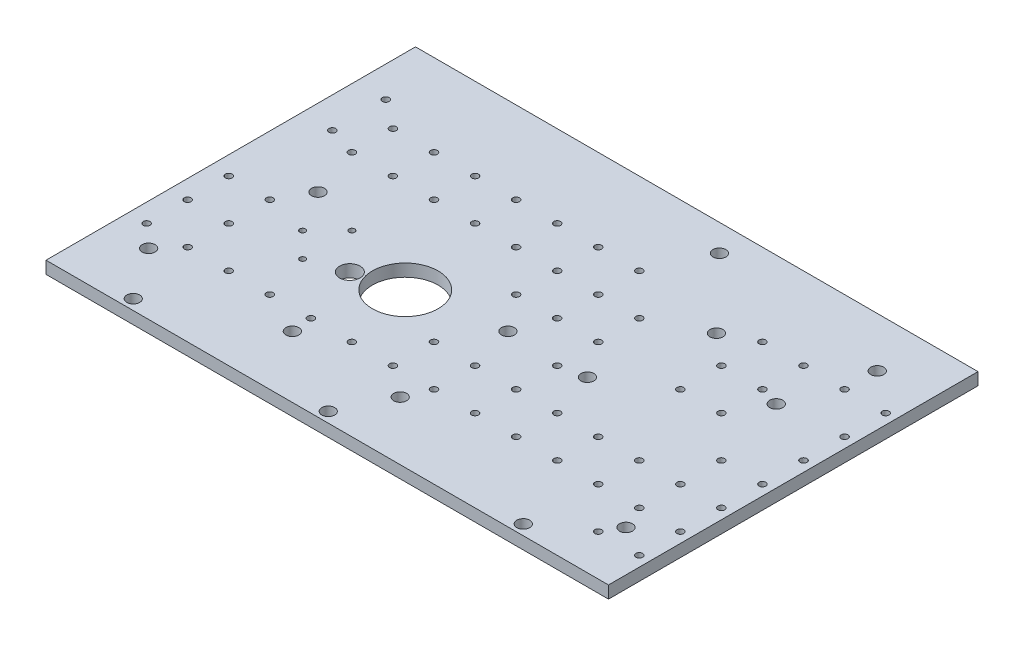
SolidWorks part; units mm, degrees
ref_plane "Front Plane" through (0, 0, 0) normal (0, 0, 1) x (1, 0, 0)
ref_plane "Top Plane" through (0, 0, 0) normal (0, 1, 0) x (1, 0, 0)
ref_plane "Right Plane" through (0, 0, 0) normal (1, 0, 0) x (0, 0, -1)
sketch "Sketch1" plane through (0, 0, 0) normal (0, 1, 0) x (1, 0, 0)
  line L0 (0, 0) -> (-137, 0) construction
  line L1 (-137, 90) -> (137, 90)
  line L2 (-137, 90) -> (-137, -90)
  line L3 (-137, -90) -> (137, -90)
  line L4 (137, 90) -> (137, -90)
  line L5 (-137, 90) -> (137, -90) construction
  line L6 (-137, -90) -> (137, 90) construction
  line L7 (-137, 25) -> (-137, -25)
  line L11 (-137, 25) -> (-137, -25)
  line L12 (11.8, 25) -> (-137, -25) construction
  line L13 (11.8, -25) -> (-137, 25) construction
  line L14 (-90, -3.3679) -> (-90, -26.6321) construction
  line L15 (-62.496, -30) -> (-28.3679, -30) construction
  line L16 (-137, 47.5) -> (-60.1856, 47.5) construction
  line L17 (-147, 75) -> (-127, 75) construction
  line L18 (-127, 20) -> (-137, 20) construction
  circle A0 centre (-75, -3) radius 1.4
  circle A1 centre (-87, -15) radius 1.4
  circle A2 centre (-75, -27) radius 1.4
  circle A3 centre (-37, -15) radius 16
  circle A4 centre (-58, -21) radius 5
  circle A5 centre (-99.5, 5) radius 3.15
  circle A6 centre (24.0972, 76.9236) radius 3.15
  circle A7 centre (5.5, -7.5) radius 3.15
  circle A8 centre (44.2412, -7.5) radius 3.15
  circle A9 centre (57.1025, 42.5) radius 3.15
  circle A10 centre (101.5049, 27.2175) radius 3.15
  circle A11 centre (112.1538, 65.774) radius 3.15
  circle A12 centre (90.5, -85) radius 3.15
  circle A13 centre (-4.5, -85) radius 3.15
  circle A14 centre (-99.5, -85) radius 3.15
  circle A15 centre (-122, 60.4986) radius 1.65
  circle A16 centre (-122, 34.5014) radius 1.65
  circle A17 centre (-117, -60) radius 3.15
  circle A18 centre (-47, -60) radius 3.15
  circle A19 centre (7, -61.4825) radius 3.15
  circle A20 centre (117, -61.4825) radius 3.15
  circle A21 centre (132, 50) radius 1.65
  circle A22 centre (132, 30) radius 1.65
  circle A23 centre (132, 10) radius 1.65
  circle A24 centre (132, -10) radius 1.65
  circle A25 centre (132, -30) radius 1.65
  circle A26 centre (132, -50) radius 1.65
  circle A27 centre (132, -70) radius 1.65
  circle A28 centre (112, 50) radius 1.65
  circle A31 centre (112, -10) radius 1.65
  circle A32 centre (112, -30) radius 1.65
  circle A33 centre (112, -50) radius 1.65
  circle A34 centre (112, -70) radius 1.65
  circle A35 centre (92, 50) radius 1.65
  circle A36 centre (92, 30) radius 1.65
  circle A37 centre (92, 10) radius 1.65
  circle A39 centre (92, -30) radius 1.65
  circle A40 centre (92, -50) radius 1.65
  circle A42 centre (72, 50) radius 1.65
  circle A43 centre (72, 30) radius 1.65
  circle A44 centre (72, 10) radius 1.65
  circle A46 centre (72, -30) radius 1.65
  circle A47 centre (72, -50) radius 1.65
  circle A53 centre (52, -30) radius 1.65
  circle A54 centre (52, -50) radius 1.65
  circle A57 centre (32, 30) radius 1.65
  circle A58 centre (32, 10) radius 1.65
  circle A59 centre (32, -10) radius 1.65
  circle A60 centre (32, -30) radius 1.65
  circle A61 centre (32, -50) radius 1.65
  circle A63 centre (12, 50) radius 1.65
  circle A64 centre (12, 30) radius 1.65
  circle A65 centre (12, 10) radius 1.65
  circle A67 centre (12, -30) radius 1.65
  circle A68 centre (12, -50) radius 1.65
  circle A70 centre (-8, 50) radius 1.65
  circle A71 centre (-8, 30) radius 1.65
  circle A72 centre (-8, 10) radius 1.65
  circle A74 centre (-8, -30) radius 1.65
  circle A75 centre (-8, -50) radius 1.65
  circle A77 centre (-28, 50) radius 1.65
  circle A78 centre (-28, 30) radius 1.65
  circle A82 centre (-28, -50) radius 1.65
  circle A84 centre (-48, 50) radius 1.65
  circle A85 centre (-48, 30) radius 1.65
  circle A89 centre (-48, -50) radius 1.65
  circle A91 centre (-68, 50) radius 1.65
  circle A92 centre (-68, 30) radius 1.65
  circle A96 centre (-68, -50) radius 1.65
  circle A98 centre (-88, 50) radius 1.65
  circle A99 centre (-88, 30) radius 1.65
  circle A103 centre (-88, -50) radius 1.65
  circle A105 centre (-108, 50) radius 1.65
  circle A106 centre (-108, 30) radius 1.65
  circle A108 centre (-108, -10) radius 1.65
  circle A109 centre (-108, -30) radius 1.65
  circle A110 centre (-108, -50) radius 1.65
  circle A115 centre (-128, -10) radius 1.65
  circle A116 centre (-128, -30) radius 1.65
  circle A117 centre (-128, -50) radius 1.65
  circle A119 centre (-128, -70) radius 1.65 [skipped]
  circle A120 centre (-108, -70) radius 1.65 [skipped]
  circle A121 centre (-88, -70) radius 1.65 [skipped]
  circle A122 centre (-68, -70) radius 1.65 [skipped]
  circle A123 centre (-48, -70) radius 1.65 [skipped]
  circle A124 centre (-8, -70) radius 1.65 [skipped]
  circle A125 centre (12, -70) radius 1.65 [skipped]
  circle A126 centre (32, -70) radius 1.65 [skipped]
  circle A127 centre (52, -70) radius 1.65 [skipped]
  circle A128 centre (72, -70) radius 1.65 [skipped]
  circle A129 centre (92, -70) radius 1.65 [skipped]
  circle A130 centre (112, 10) radius 1.65 [skipped]
  circle A131 centre (112, 30) radius 1.65 [skipped]
  circle A132 centre (-28, -70) radius 1.65 [skipped]
  circle A133 centre (-88, -10) radius 1.65 [skipped]
  circle A134 centre (-68, -10) radius 1.65 [skipped]
  circle A135 centre (-68, -30) radius 1.65 [skipped]
  circle A136 centre (-88, -30) radius 1.65 [skipped]
  circle A137 centre (-48, -10) radius 1.65 [skipped]
  circle A138 centre (-28, -10) radius 1.65 [skipped]
  circle A139 centre (-28, -30) radius 1.65 [skipped]
  circle A140 centre (-48, -30) radius 1.65 [skipped]
  circle A141 centre (32, 50) radius 1.65 [skipped]
  circle A142 centre (52, 30) radius 1.65 [skipped]
  circle A143 centre (52, 50) radius 1.65 [skipped]
  circle A144 centre (52, 10) radius 1.65 [skipped]
  circle A145 centre (52, -10) radius 1.65 [skipped]
  circle A146 centre (72, -10) radius 1.65 [skipped]
  circle A147 centre (92, -10) radius 1.65 [skipped]
  circle A148 centre (-8, -10) radius 1.65 [skipped]
  circle A149 centre (-28, 10) radius 1.65 [skipped]
  circle A150 centre (-48, 10) radius 1.65 [skipped]
  circle A151 centre (-68, 10) radius 1.65 [skipped]
  circle A152 centre (-88, 10) radius 1.65 [skipped]
  circle A153 centre (-108, 10) radius 1.65 [skipped]
  circle A154 centre (-128, 10) radius 1.65 [skipped]
  circle A155 centre (12, -10) radius 1.65 [skipped]
  circle A156 centre (-128, 50) radius 1.65 [skipped]
  circle A157 centre (-128, 30) radius 1.65 [skipped]
  point P0 (0, 0)
  point P8 (-62.6, 0)
  dimension "D3" = 32
  dimension "D4" = 2.8
  dimension "D5" = 10
  dimension "D6" = 32
  dimension "D8" = 3.3
  dimension "D10" = 6.3
  dimension "D11" = 20
  dimension "D16" = 3.3
  dimension "D1" = 180
  dimension "D2" = 274
  dimension "D7" = 9
  dimension "D9" = 15
  dimension "D12" = 20
  dimension "D13" = 70
  dimension "D14" = 110
  dimension "D15" = 30
  dimension "D17" = 20
  dimension "D18" = 20
  dimension "D19" = 20
  dimension "D20" = 20
  dimension "D21" = 40
  dimension "D22" = 20
  dimension "D23" = 20
  dimension "D24" = 5
  dimension "D25" = 14
extrude "Boss-Extrude1" add sketch "Sketch1" along normal blind 6
